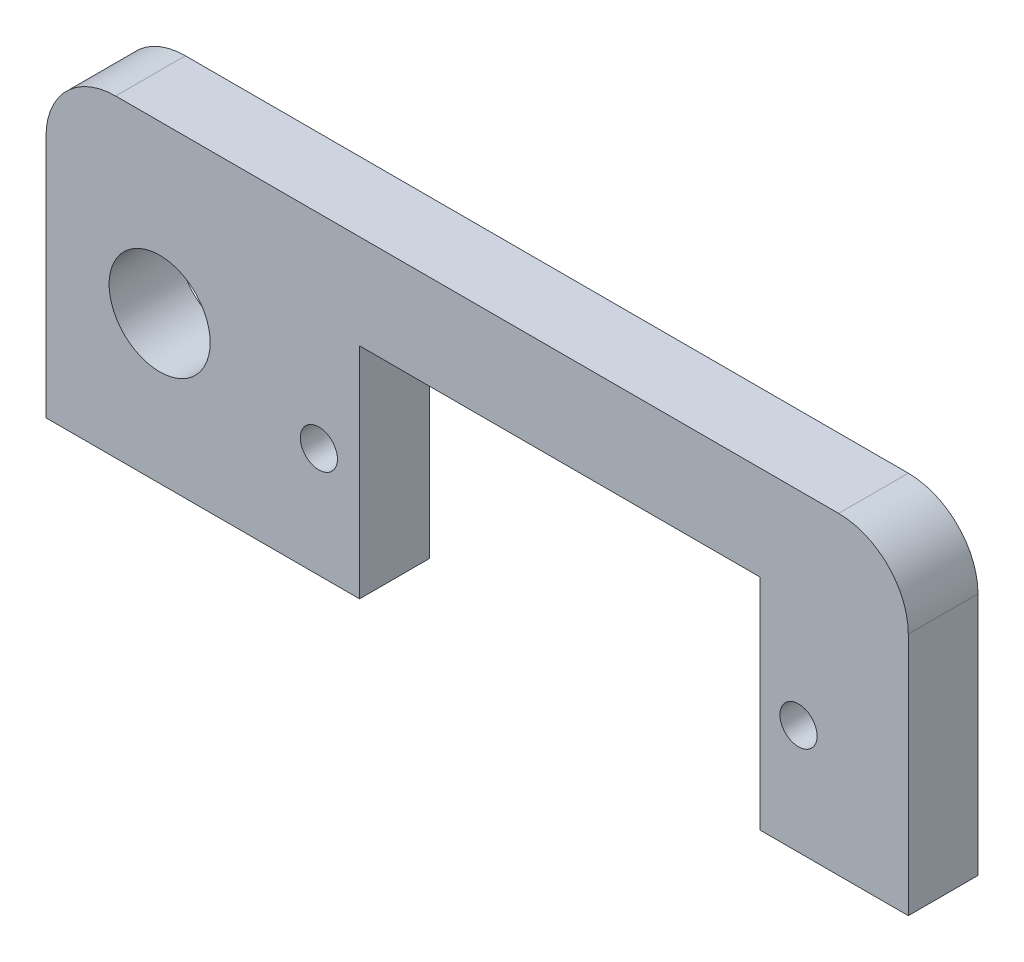
SolidWorks part; units mm, degrees
ref_plane "Front Plane" through (0, 0, 0) normal (0, 0, 1) x (1, 0, 0)
ref_plane "Top Plane" through (0, 0, 0) normal (0, 1, 0) x (1, 0, 0)
ref_plane "Right Plane" through (0, 0, 0) normal (1, 0, 0) x (0, 0, -1)
sketch "Sketch1" plane through (0, 0, 0) normal (0, 0, 1) x (1, 0, 0)
  line L1 (0, 0) -> (23, 0)
  line L2 (0, 0) -> (0, 12.58)
  line L3 (0, 12.58) -> (23, 12.58)
  line L4 (23, 0) -> (23, 12.58)
  line L5 (-18, 0) -> (31.5, 0)
  line L6 (-18, 0) -> (-18, 14)
  line L7 (-14, 18) -> (27.5, 18)
  line L8 (31.5, 0) -> (31.5, 14)
  arc A0 (-18, 14) -> (-14, 18) centre (-14, 14) cw
  arc A1 (27.5, 18) -> (31.5, 14) centre (27.5, 14) cw
  point P11 (-18, 18)
  dimension "D6" = 4
  dimension "D1" = 23
  dimension "D2" = 12.58
  dimension "D3" = 18
  dimension "D4" = 8.5
  dimension "D5" = 18
extrude "Boss-Extrude1" add sketch "Sketch1" along normal blind 4 contours A1 L7 A0 L6 L5 L2 L3 L4 L8
sketch "Sketch2" plane through (0, 0, 4) normal (0, 0, 1) x (1, 0, 0)
  circle A0 centre (25.1968, 6.3119) radius 1.0668 construction
  circle A2 centre (-2.3368, 6.3119) radius 1.0668 construction
  circle A3 centre (25.1968, 6.3119) radius 1.0668
  circle A4 centre (-11.476, 8.45) radius 2.9 construction
  circle A5 centre (-2.3368, 6.3119) radius 1.0668
  circle A6 centre (-11.476, 8.45) radius 2.9
extrude "Cut-Extrude1" cut sketch "Sketch2" against normal blind 4
